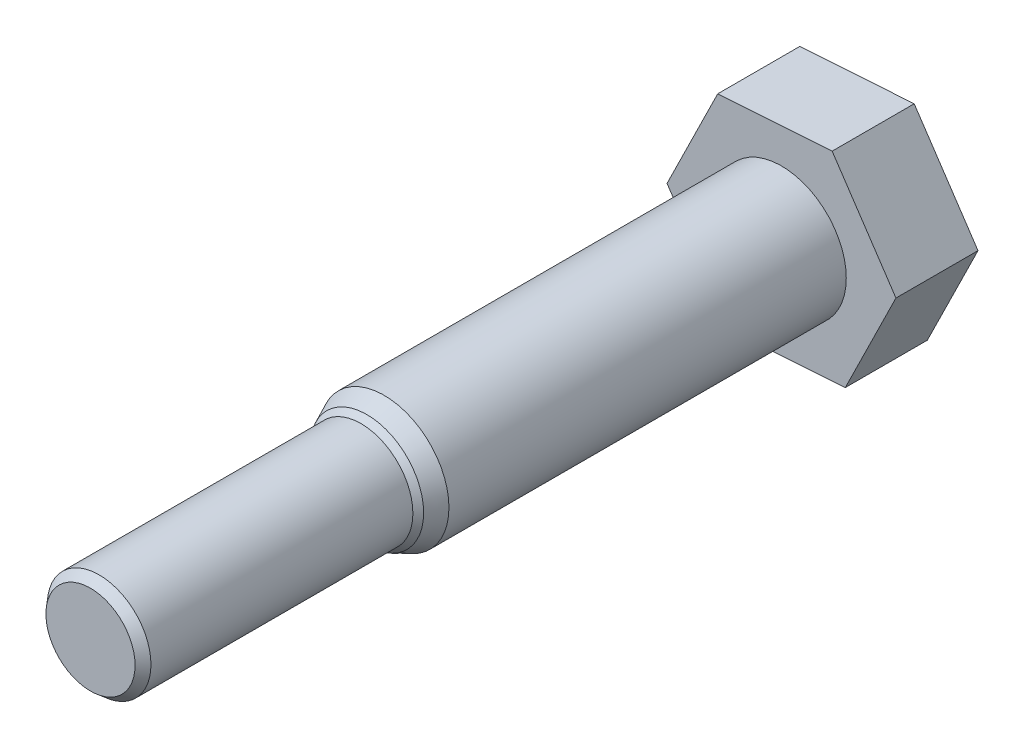
SolidWorks part; units mm, degrees
ref_plane "前视基准面" through (0, 0, 0) normal (0, 0, 1) x (1, 0, 0)
ref_plane "上视基准面" through (0, 0, 0) normal (0, 1, 0) x (1, 0, 0)
ref_plane "右视基准面" through (0, 0, 0) normal (1, 0, 0) x (0, 0, -1)
sketch "草图1" plane through (0, 0, 0) normal (0, 0, 1) x (1, 0, 0)
  circle A0 centre (0, 0) radius 15
  dimension "D1" = 30
extrude "拉伸1" add sketch "草图1" along normal blind 111
sketch "草图2" plane through (0, 0, 0) normal (0, 0, 1) x (1, 0, 0)
  line L1 (14.7707, -22.0717) -> (26.5, 1.7559)
  line L2 (26.5, 1.7559) -> (11.7293, 23.8276)
  line L3 (11.7293, 23.8276) -> (-14.7707, 22.0717)
  line L4 (-14.7707, 22.0717) -> (-26.5, -1.7559)
  line L5 (-26.5, -1.7559) -> (-11.7293, -23.8276)
  line L6 (-11.7293, -23.8276) -> (14.7707, -22.0717)
  circle A0 centre (0, 0) radius 23 construction
  dimension "D1" = 46
  dimension "D2" = 53
extrude "拉伸2" add sketch "草图2" along normal blind 19
sketch "草图7" plane through (0, 0, 111) normal (0, 0, 1) x (1, 0, 0)
  circle A0 centre (0, 0) radius 15
  dimension "D1" = 30
extrude "拉伸4" add sketch "草图7" along normal blind 4 draft 25
sketch "草图22" plane through (0, 0, 115) normal (0, 0, 1) x (1, 0, 0)
  circle A0 centre (0, 0) radius 12
  dimension "D1" = 24
extrude "拉伸22" add sketch "草图22" along normal blind 62
sketch "草图23" plane through (0, 0, 115) normal (0, 0, 1) x (1, 0, 0)
  circle A1 centre (0, 0) radius 13.1348
  dimension "D1" = 26.2695
extrude "拉伸24" add sketch "草图23" along normal blind 2 draft 40
sketch "草图24" plane through (0, 0, 177) normal (0, 0, 1) x (1, 0, 0)
  circle A0 centre (0, 0) radius 12
  dimension "D1" = 24
extrude "拉伸25" add sketch "草图24" along normal blind 2 draft 40
